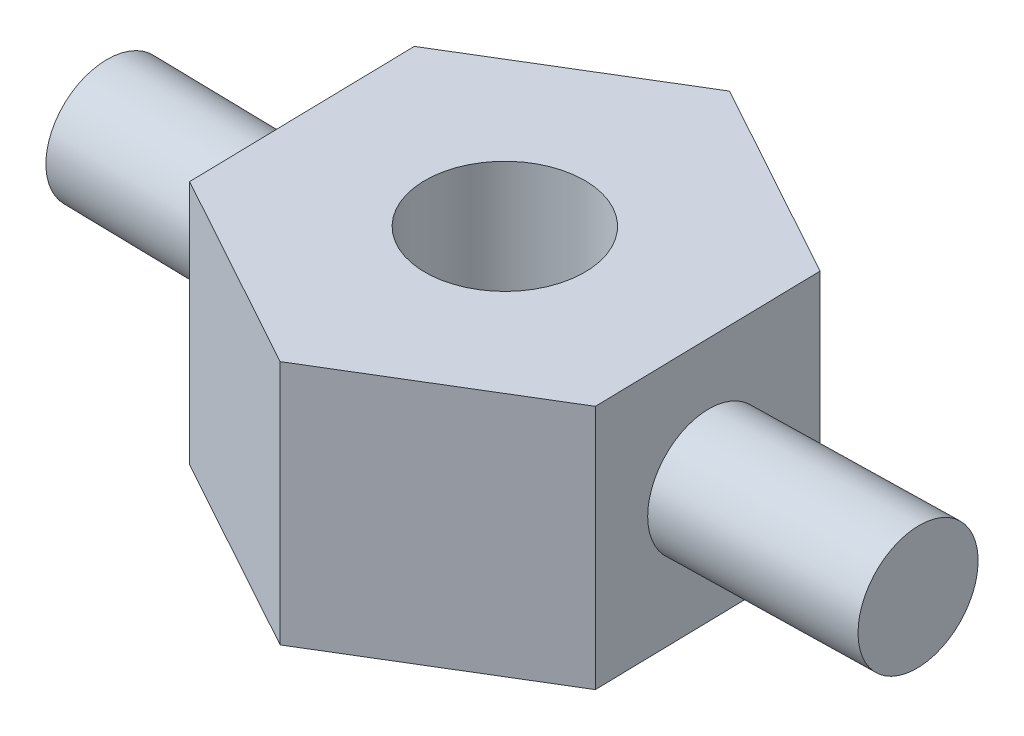
SolidWorks part; units mm, degrees
ref_plane "Front Plane" through (0, 0, 0) normal (0, 0, 1) x (1, 0, 0)
ref_plane "Top Plane" through (0, 0, 0) normal (0, 1, 0) x (1, 0, 0)
ref_plane "Right Plane" through (0, 0, 0) normal (1, 0, 0) x (0, 0, -1)
sketch "Sketch5" plane through (0, 0, 0) normal (0, 1, 0) x (1, 0, 0)
  line L1 (-80.0256, -48.453) -> (1.9487, -93.5307)
  line L2 (1.9487, -93.5307) -> (81.9744, -45.0777)
  line L3 (81.9744, -45.0777) -> (80.0256, 48.453)
  line L4 (80.0256, 48.453) -> (-1.9487, 93.5307)
  line L5 (-1.9487, 93.5307) -> (-81.9744, 45.0777)
  line L6 (-81.9744, 45.0777) -> (-80.0256, -48.453)
  circle A0 centre (0, 0) radius 81.0176 construction
  dimension "D1" = 162
extrude "Boss-Extrude1" add sketch "Sketch5" along normal blind 100
sketch "Sketch6" plane through (0, 0, 0) normal (0, -1, 0) x (-1, 0, 0)
  circle A1 centre (0, 0) radius 32.5
  dimension "D1" = 65
extrude "Cut-Extrude1" cut sketch "Sketch6" against normal through all
sketch "Sketch7" plane through (81, 0, -1.6876) normal (0.9998, 0, -0.0208) x (-0.0208, 0, -0.9998)
  circle A1 centre (0, 50) radius 25
  dimension "D1" = 50
extrude "Boss-Extrude2" add sketch "Sketch7" along normal blind 84
mirror "Mirror1" about plane through (0, 0, 0) normal (1, 0, 0) of "Boss-Extrude2"
equation "\"`100\"=73.6023"
